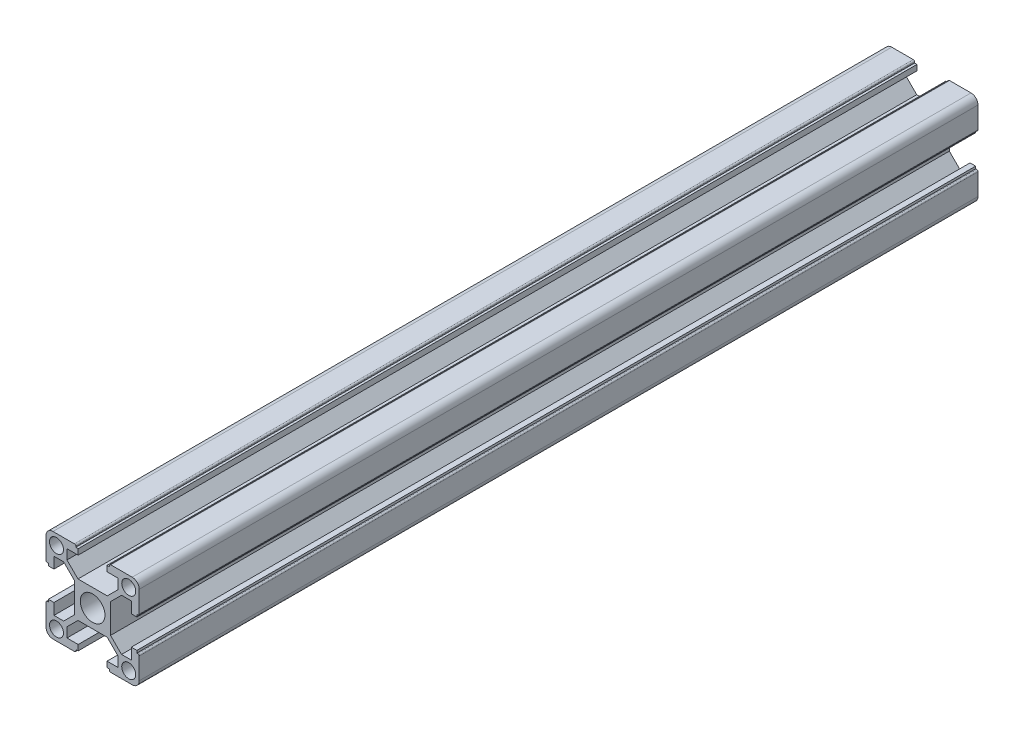
SolidWorks part; units mm, degrees
ref_plane "前视基准面" through (0, 0, 0) normal (0, 0, 1) x (1, 0, 0)
ref_plane "上视基准面" through (0, 0, 0) normal (0, 1, 0) x (1, 0, 0)
ref_plane "右视基准面" through (0, 0, 0) normal (1, 0, 0) x (0, 0, -1)
sketch "草图1" plane through (0, 0, 0) normal (0, 0, 1) x (1, 0, 0)
  line L0 (-7.75, 0) -> (0, 0) construction
  line L1 (7.75, -7.75) -> (-7.75, -7.75) construction
  line L2 (7.75, -7.75) -> (7.75, 7.75) construction
  line L3 (7.75, 7.75) -> (-7.75, 7.75) construction
  line L4 (-7.75, -7.75) -> (-7.75, 7.75) construction
  line L5 (7.75, -7.75) -> (-7.75, 7.75) construction
  line L6 (7.75, 7.75) -> (-7.75, -7.75) construction
  line L7 (0, 0) -> (0, 7.75) construction
  line L8 (3.1429, 3.85) -> (-3.1429, 3.85)
  line L9 (-3.1429, 3.85) -> (-5.5, 6.2071)
  line L10 (-5.5, 6.2071) -> (-5.5, 8.3)
  line L11 (-5.5, 8.3) -> (-3.1, 8.3)
  line L12 (-3.1, 8.3) -> (-3.1, 9.5)
  line L13 (-3.1, 9.5) -> (-3.6, 9.5)
  line L14 (-3.6, 9.5) -> (-3.6, 9.7)
  line L15 (-3.9, 10) -> (-8.5, 10)
  line L16 (-3.85, -3.1429) -> (-3.85, 3.1429)
  line L17 (-3.85, 3.1429) -> (-6.2071, 5.5)
  line L18 (-6.2071, 5.5) -> (-8.3, 5.5)
  line L19 (-8.3, 5.5) -> (-8.3, 3.1)
  line L20 (-9.5, 3.1) -> (-9.5, 3.6)
  line L21 (-8.3, 3.1) -> (-9.5, 3.1)
  line L22 (-9.5, 3.6) -> (-9.7, 3.6)
  line L23 (-10, 3.9) -> (-10, 8.5)
  line L24 (5.5, 8.3) -> (3.1, 8.3)
  line L25 (3.6, 9.5) -> (3.6, 9.7)
  line L26 (3.1, 9.5) -> (3.6, 9.5)
  line L27 (3.1, 8.3) -> (3.1, 9.5)
  line L28 (5.5, 6.2071) -> (5.5, 8.3)
  line L29 (3.1429, 3.85) -> (5.5, 6.2071)
  line L30 (3.85, -3.1429) -> (3.85, 3.1429)
  line L31 (3.85, 3.1429) -> (6.2071, 5.5)
  line L32 (9.5, 3.6) -> (9.7, 3.6)
  line L33 (8.3, 3.1) -> (9.5, 3.1)
  line L34 (9.5, 3.1) -> (9.5, 3.6)
  line L35 (8.3, 5.5) -> (8.3, 3.1)
  line L36 (6.2071, 5.5) -> (8.3, 5.5)
  line L37 (10, 3.9) -> (10, 8.5)
  line L38 (3.9, 10) -> (8.5, 10)
  line L39 (-9.5, -3.6) -> (-9.7, -3.6)
  line L40 (-8.3, -3.1) -> (-9.5, -3.1)
  line L41 (-9.5, -3.1) -> (-9.5, -3.6)
  line L42 (-8.3, -5.5) -> (-8.3, -3.1)
  line L43 (-6.2071, -5.5) -> (-8.3, -5.5)
  line L44 (-3.85, -3.1429) -> (-6.2071, -5.5)
  line L45 (-3.1429, -3.85) -> (-5.5, -6.2071)
  line L46 (-5.5, -6.2071) -> (-5.5, -8.3)
  line L47 (-3.6, -9.5) -> (-3.6, -9.7)
  line L48 (-3.1, -9.5) -> (-3.6, -9.5)
  line L49 (-3.1, -8.3) -> (-3.1, -9.5)
  line L50 (-5.5, -8.3) -> (-3.1, -8.3)
  line L51 (5.5, -6.2071) -> (5.5, -8.3)
  line L52 (3.1, -8.3) -> (3.1, -9.5)
  line L53 (3.1, -9.5) -> (3.6, -9.5)
  line L54 (3.6, -9.5) -> (3.6, -9.7)
  line L55 (5.5, -8.3) -> (3.1, -8.3)
  line L56 (3.1429, -3.85) -> (5.5, -6.2071)
  line L57 (3.1429, -3.85) -> (-3.1429, -3.85)
  line L58 (3.85, -3.1429) -> (6.2071, -5.5)
  line L59 (6.2071, -5.5) -> (8.3, -5.5)
  line L60 (8.3, -5.5) -> (8.3, -3.1)
  line L61 (9.5, -3.1) -> (9.5, -3.6)
  line L62 (8.3, -3.1) -> (9.5, -3.1)
  line L63 (9.5, -3.6) -> (9.7, -3.6)
  line L64 (3.9, -10) -> (8.5, -10)
  line L65 (10, -3.9) -> (10, -8.5)
  line L66 (-10, -3.9) -> (-10, -8.5)
  line L67 (-3.9, -10) -> (-8.5, -10)
  circle A0 centre (0, 0) radius 2.65
  circle A1 centre (-7.75, 7.75) radius 1.5
  circle A2 centre (7.75, 7.75) radius 1.5
  circle A3 centre (7.75, -7.75) radius 1.5
  circle A4 centre (-7.75, -7.75) radius 1.5
  arc A5 (-10, -8.5) -> (-8.5, -10) centre (-8.5, -8.5) ccw
  arc A6 (8.5, -10) -> (10, -8.5) centre (8.5, -8.5) ccw
  arc A7 (10, 8.5) -> (8.5, 10) centre (8.5, 8.5) ccw
  arc A8 (-8.5, 10) -> (-10, 8.5) centre (-8.5, 8.5) ccw
  arc A9 (3.6, -9.7) -> (3.9, -10) centre (3.9, -9.7) ccw
  arc A10 (-3.6, -9.7) -> (-3.9, -10) centre (-3.9, -9.7) cw
  arc A11 (-9.7, -3.6) -> (-10, -3.9) centre (-9.7, -3.9) ccw
  arc A12 (9.7, -3.6) -> (10, -3.9) centre (9.7, -3.9) cw
  arc A13 (9.7, 3.6) -> (10, 3.9) centre (9.7, 3.9) ccw
  arc A14 (-9.7, 3.6) -> (-10, 3.9) centre (-9.7, 3.9) cw
  arc A15 (3.6, 9.7) -> (3.9, 10) centre (3.9, 9.7) cw
  arc A16 (-3.6, 9.7) -> (-3.9, 10) centre (-3.9, 9.7) ccw
  point P46 (0, 3.85)
  point P56 (-3.85, 0)
  point P78 (3.85, 0)
  point P87 (-10, -10)
  point P90 (10, -10)
  point P93 (10, 10)
  point P96 (-10, 10)
  point P99 (3.6, -10)
  point P102 (-3.6, -10)
  point P105 (-10, -3.6)
  point P108 (10, -3.6)
  point P111 (10, 3.6)
  point P114 (-10, 3.6)
  point P117 (3.6, 10)
  point P120 (-3.6, 10)
  dimension "D1" = 5.3
  dimension "D2" = 3
  dimension "D11" = 1.5
  dimension "D12" = 2.25
  dimension "D13" = 0.3
  dimension "D3" = 7.7
  dimension "D4" = 6.2
  dimension "D5" = 1.7
  dimension "D6" = 1.2
  dimension "D7" = 20
  dimension "D8" = 7.2
  dimension "D9" = 11
  dimension "D10" = 1
extrude "凸台-拉伸1" add sketch "草图1" along normal mid plane 180
